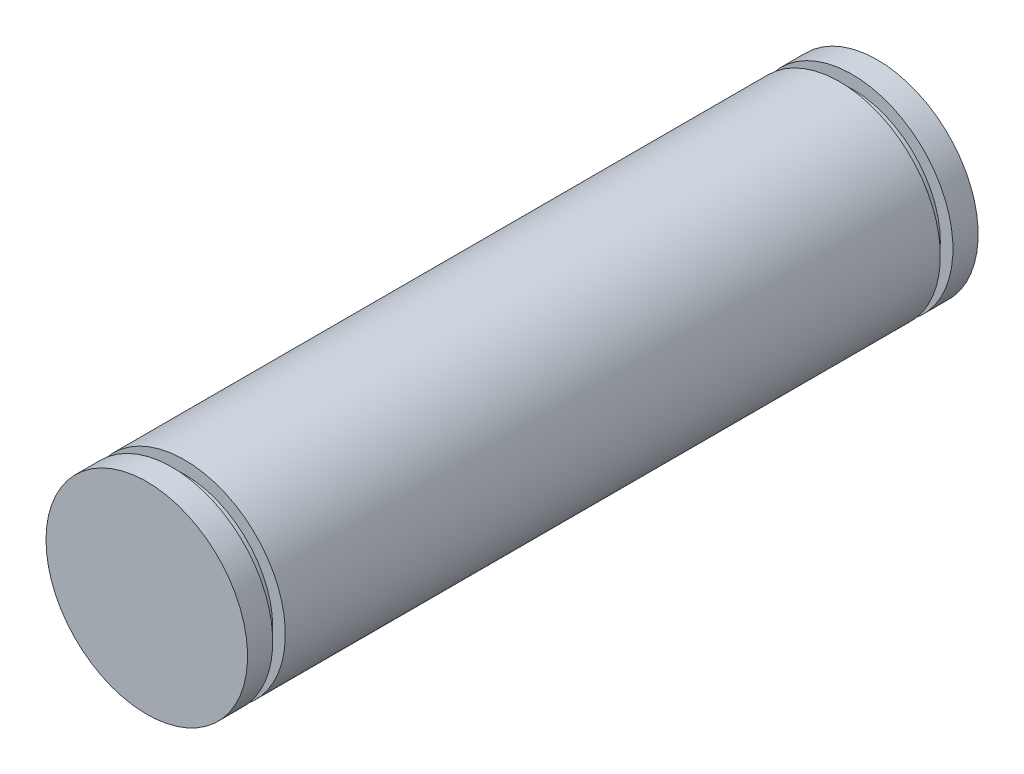
SolidWorks part; units mm, degrees
ref_plane "Front Plane" through (0, 0, 0) normal (0, 0, 1) x (1, 0, 0)
ref_plane "Top Plane" through (0, 0, 0) normal (0, 1, 0) x (1, 0, 0)
ref_plane "Right Plane" through (0, 0, 0) normal (1, 0, 0) x (0, 0, -1)
sketch "Sketch1" plane through (0, 0, 0) normal (0, 0, 1) x (1, 0, 0)
  circle A0 centre (0, 0) radius 8
extrude "Boss-Extrude1" add sketch "Sketch1" along normal blind 58
ref_plane "Plane1" through (0, 0, 56) normal (0, 0, 1) x (1, 0, 0)
sketch "Sketch2" plane through (0, 0, 56) normal (0, 0, 1) x (1, 0, 0)
  circle A0 centre (0, 0) radius 7
extrude "Cut-Extrude1" cut sketch "Sketch2" against normal blind 1 flip side to cut
ref_plane "Plane2" through (0, 0, 29) normal (0, 0, 1) x (1, 0, 0)
mirror "Mirror1" about plane through (0, 0, 29) normal (0, 0, 1) of "Cut-Extrude1"
